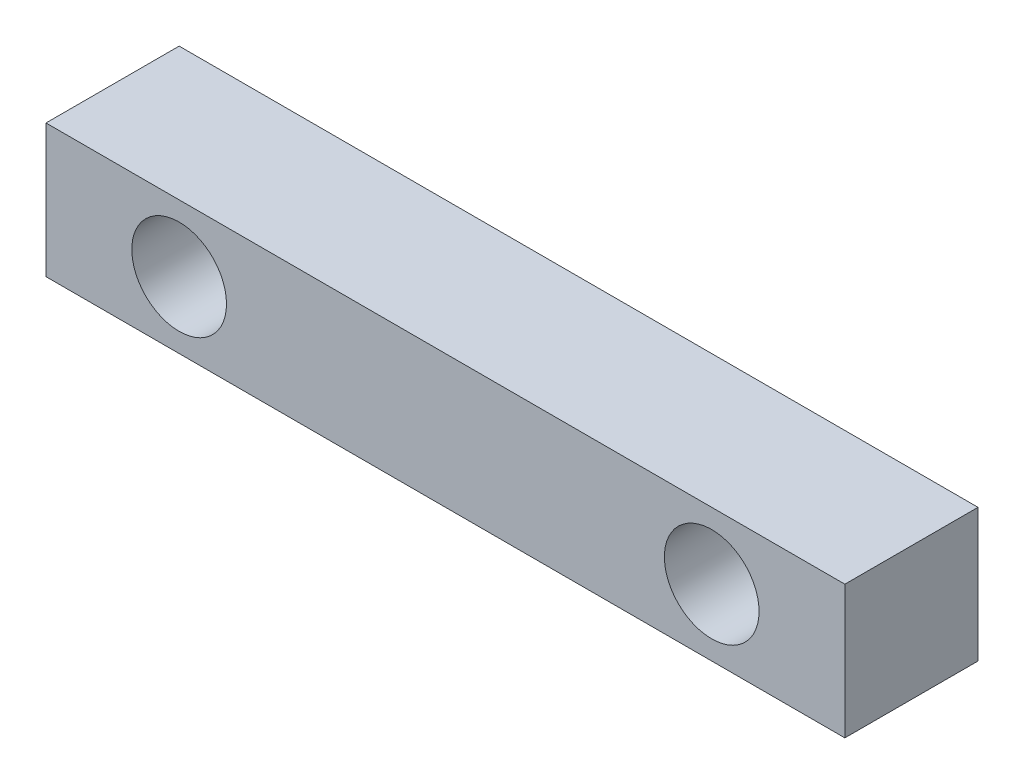
SolidWorks part; units mm, degrees
ref_plane "Front Plane" through (0, 0, 0) normal (0, 0, 1) x (1, 0, 0)
ref_plane "Top Plane" through (0, 0, 0) normal (0, 1, 0) x (1, 0, 0)
ref_plane "Right Plane" through (0, 0, 0) normal (1, 0, 0) x (0, 0, -1)
sketch "Sketch1" plane through (0, 0, 0) normal (0, 0, 1) x (1, 0, 0)
  line L1 (-15, 2.5) -> (15, 2.5)
  line L2 (-15, 2.5) -> (-15, -2.5)
  line L3 (-15, -2.5) -> (15, -2.5)
  line L4 (15, 2.5) -> (15, -2.5)
  point P4 (0, 2.5)
  point P6 (-15, 0)
  dimension "D1" = 30
  dimension "D2" = 5
extrude "Boss-Extrude1" add sketch "Sketch1" along normal blind 5
hole_wizard "5/32 (0.14) Diameter Hole1" positions "Sketch2" profile "Sketch3" hole size "5/32" standard "ANSI Inch" end condition through all
sketch "Sketch2" plane through (0, 0, 5) normal (0, 0, 1) x (1, 0, 0)
  line L0 (-10, 0) -> (10, 0) construction
  point P0 (-10, 0)
  point P2 (10, 0)
  point P10 (0, 0)
  dimension "D1" = 20
sketch "Sketch3" plane through (-10, 0, 5) normal (1, 0, 0) x (0, -1, 0)
  line L0 (0, 0) -> (0, 5)
  line L1 (0, 5) -> (1.778, 5)
  line L2 (1.778, 5) -> (1.778, 0)
  line L5 (1.778, 0) -> (0, 0)
  line L11 (0, -6.35) -> (0, 107.95) construction
  dimension "Thru Hole Dia." = 3.556
  dimension "Thru Hole Depth" = 5
